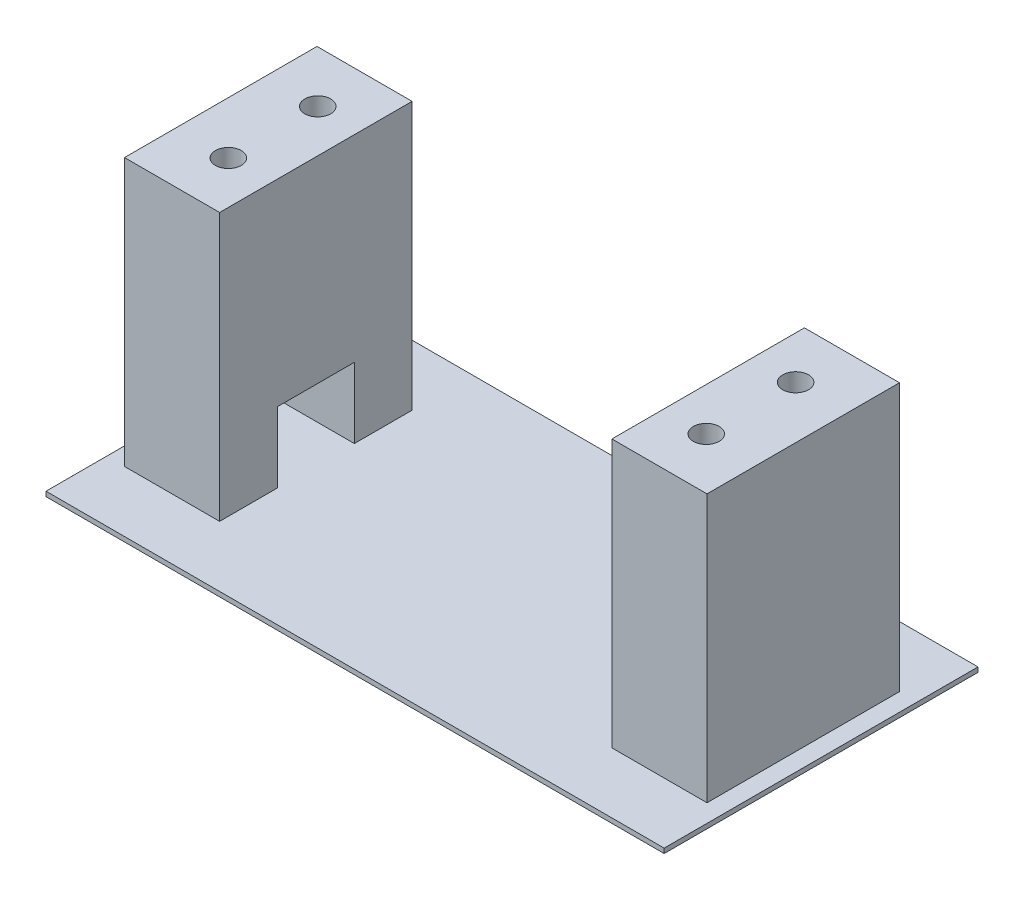
SolidWorks part; units mm, degrees
ref_plane "Front Plane" through (0, 0, 0) normal (0, 0, 1) x (1, 0, 0)
ref_plane "Top Plane" through (0, 0, 0) normal (0, 1, 0) x (1, 0, 0)
ref_plane "Right Plane" through (0, 0, 0) normal (1, 0, 0) x (0, 0, -1)
sketch "Sketch1" plane through (0, 0, 0) normal (0, 1, 0) x (1, 0, 0)
  line L1 (-32.5, -16.5) -> (32.5, -16.5)
  line L2 (-32.5, -16.5) -> (-32.5, 16.5)
  line L3 (-32.5, 16.5) -> (32.5, 16.5)
  line L4 (32.5, -16.5) -> (32.5, 16.5)
  line L5 (-32.5, -16.5) -> (32.5, 16.5) construction
  line L6 (-32.5, 16.5) -> (32.5, -16.5) construction
  point P0 (0, 0)
  dimension "D1" = 33
  dimension "D2" = 65
extrude "Boss-Extrude1" add sketch "Sketch1" along normal blind 0.5
sketch "Sketch2" plane through (0, 0.5, 0) normal (0, 1, 0) x (1, 0, 0)
  line L1 (-20.625, -10.12) -> (20.625, -10.12) construction
  line L2 (-20.625, -10.12) -> (-20.625, 10.12) construction
  line L3 (-20.625, 10.12) -> (20.625, 10.12) construction
  line L4 (20.625, -10.12) -> (20.625, 10.12) construction
  line L5 (-20.625, -10.12) -> (20.625, 10.12) construction
  line L6 (-20.625, 10.12) -> (20.625, -10.12) construction
  line L7 (20.625, 10.12) -> (30.625, 10.12)
  line L8 (20.625, 10.12) -> (20.625, -10.12)
  line L9 (20.625, -10.12) -> (30.625, -10.12)
  line L10 (30.625, 10.12) -> (30.625, -10.12)
  point P0 (0, 0)
  dimension "D1" = 41.25
  dimension "D2" = 20.24
  dimension "D3" = 10
extrude "Boss-Extrude2" add sketch "Sketch2" along normal blind 28.13 contours L8 L7 L10 L9
sketch "Sketch3" plane through (0, 28.63, 0) normal (0, 1, 0) x (1, 0, 0)
  line L0 (20.625, 0) -> (30.625, 0) construction
  line L1 (20.625, 10.12) -> (20.625, -10.12) construction
  line L2 (30.625, 10.12) -> (30.625, -10.12) construction
  line L3 (20.625, 10.12) -> (20.625, -10.12) construction
  circle A0 centre (25.125, 4.7) radius 1.3611
  circle A1 centre (25.125, -4.7) radius 1.3611
  dimension "D1" = 4.7
  dimension "D2" = 4.5
extrude "Cut-Extrude1" cut sketch "Sketch3" against normal blind 10 and the other way through all
mirror "Mirror3" about plane through (0, 0, 0) normal (1, 0, 0) of "Cut-Extrude1", "Boss-Extrude2"
sketch "Sketch4" plane through (-30.625, 0, 0) normal (-1, 0, 0) x (0, 0, 1)
  line L0 (-10.12, 0.5) -> (10.12, 0.5) construction
  line L1 (-4.05, 7.9) -> (4.05, 7.9)
  line L2 (-4.05, 7.9) -> (-4.05, 0.5)
  line L3 (-4.05, 0.5) -> (4.05, 0.5)
  line L4 (4.05, 7.9) -> (4.05, 0.5)
  line L5 (-4.05, 7.9) -> (4.05, 0.5) construction
  line L6 (-4.05, 0.5) -> (4.05, 7.9) construction
  line L7 (0, 0) -> (0, 10.6191) construction
  point P0 (0, 4.2)
  dimension "D1" = 8.1
  dimension "D2" = 7.4
extrude "Cut-Extrude2" cut sketch "Sketch4" against normal up to next
